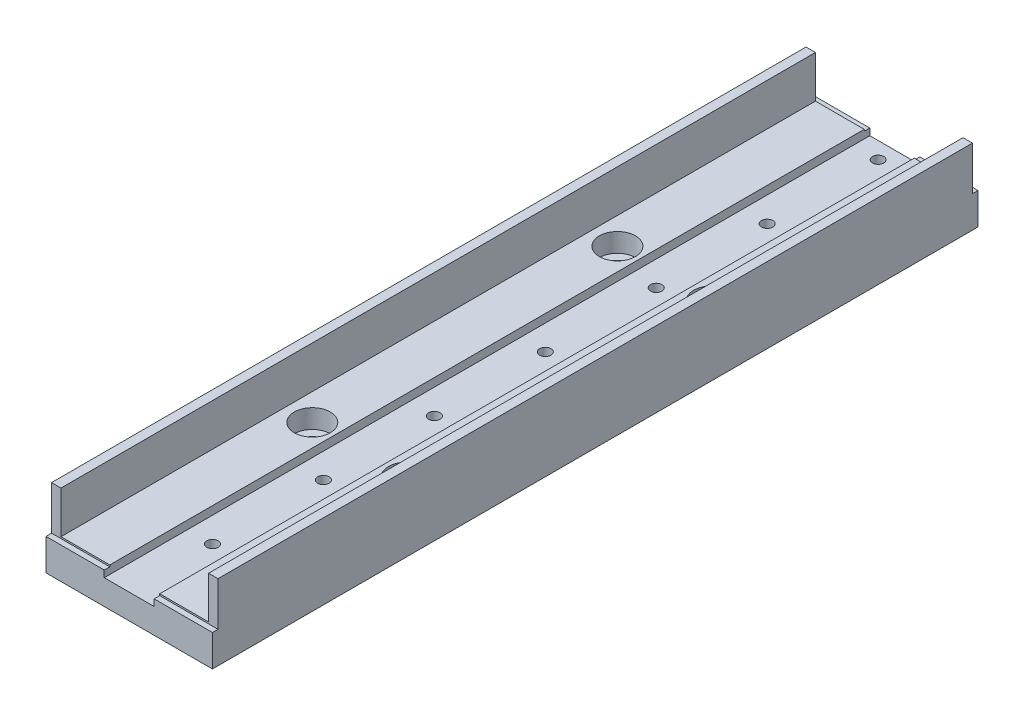
SolidWorks part; units mm, degrees
ref_plane "Спереди" through (0, 0, 0) normal (0, 0, 1) x (1, 0, 0)
ref_plane "Сверху" through (0, 0, 0) normal (0, 1, 0) x (1, 0, 0)
ref_plane "Справа" through (0, 0, 0) normal (1, 0, 0) x (0, 0, -1)
sketch "Эскиз1" plane through (0, 0, 0) normal (0, 0, 1) x (1, 0, 0)
  line L0 (0, 0) -> (0, 13.1204) construction
  line L1 (-15, -3) -> (15, -3)
  line L2 (-15, -3) -> (-15, 3)
  line L3 (-13.3, 3) -> (-4.5, 3)
  line L4 (15, -3) -> (15, 3)
  line L5 (-15, -3) -> (0, 0) construction
  line L6 (0, 0) -> (15, -3) construction
  line L8 (-15, 3) -> (-15, 10.6)
  line L9 (-15, 10.6) -> (-13.3, 10.6)
  line L10 (-13.3, 3) -> (-13.3, 10.6)
  line L11 (15, 10.6) -> (13.3, 10.6)
  line L12 (13.3, 3) -> (13.3, 10.6)
  line L13 (15, 3) -> (15, 10.6)
  line L14 (-4.5, 3) -> (-4.5, 1.5)
  line L15 (-4.5, 1.5) -> (4.5, 1.5)
  line L16 (4.5, 1.5) -> (4.5, 3)
  line L17 (4.5, 3) -> (13.3, 3)
  point P0 (0, 0)
  dimension "D1" = 30
  dimension "D2" = 6
  dimension "D3" = 7.6
  dimension "D4" = 1.7
  dimension "D5" = 9
  dimension "D6" = 1.5
extrude "Body" add sketch "Эскиз1" along normal blind 138
sketch "Эскиз2" plane through (0, 10.6, 0) normal (0, 1, 0) x (1, 0, 0)
  line L0 (15, -138) -> (15, 0) construction
  line L1 (-15, -138) -> (15, -138)
  line L2 (-15, -138) -> (-15, -137)
  line L3 (-15, -137) -> (15, -137)
  line L4 (15, -138) -> (15, -137)
  line L5 (-15, -69) -> (15, -69) construction
  line L6 (-15, -138) -> (-15, 0) construction
  line L7 (15, 0) -> (15, -1)
  line L8 (-15, -1) -> (15, -1)
  line L9 (-15, 0) -> (-15, -1)
  line L10 (-15, 0) -> (15, 0)
  dimension "D1" = 1
extrude "Cut1" cut sketch "Эскиз2" against normal offset from surface (7.9 mm away) 0.3 up to face at (-8.9, 3, 69) offset beyond the face yes
sketch "Эскиз3" plane through (0, 3, 0) normal (0, 1, 0) x (1, 0, 0)
  line L0 (0, 0) -> (0, -138) construction
  line L1 (4.5, -138) -> (-4.5, -138) construction
  line L2 (0, -69) -> (15, -69) construction
  line L3 (15, -137) -> (15, -1) construction
  point P3 (8.5, -41.5)
  point P6 (-8.5, -41.5)
  point P7 (8.5, -96.5)
  point P9 (-8.5, -96.5)
  dimension "D1" = 55
  dimension "D2" = 17
hole_wizard "Fixture M3" positions "Трехмерный эскиз1" profile "Эскиз4" counterbore size "M3" standard "ISO"
sketch3d "Трехмерный эскиз1"
  point P0 (-8.5, 3, 96.5)
  point P3 (8.5, 3, 96.5)
  point P6 (8.5, 3, 41.5)
  point P9 (-8.5, 3, 41.5)
sketch "Эскиз4" plane through (-8.5, 3, 96.5) normal (1, 0, 0) x (0, 0, 1)
  line L0 (0, 0) -> (0, 7.0215)
  line L1 (0, 7.0215) -> (1.7, 6)
  line L2 (1.7, 6) -> (1.7, 3.4)
  line L3 (1.7, 3.4) -> (3.25, 3.4)
  line L4 (3.25, 3.4) -> (3.25, 0)
  line L5 (3.25, 0) -> (0, 0)
  line L10 (0, 7.0215) -> (-1.7, 6) construction
  line L11 (0, -6.35) -> (0, 107.95) construction
  dimension "Диаметр отверстия" = 3.4
  dimension "Глубина отверстия" = 6
  dimension "Диаметр цековки" = 6.5
  dimension "Глубина цековки" = 3.4
  dimension "Угол заточки сверла" = 118
sketch "Эскиз6" plane through (0, 1.5, 0) normal (0, 1, 0) x (1, 0, 0)
  line L0 (0, 0) -> (0, -138) construction
  line L1 (4.5, -138) -> (-4.5, -138) construction
  point P0 (0, -123)
  dimension "D1" = 15
hole_wizard "Fixture M2" positions "Трехмерный эскиз2" profile "Эскиз7" tap size "M2.5" standard "ISO"
sketch3d "Трехмерный эскиз2"
  point P0 (0, 1.5, 123)
sketch "Эскиз7" plane through (0, 1.5, 123) normal (1, 0, 0) x (0, 0, 1)
  line L0 (0, 0) -> (0, 5.1159)
  line L1 (0, 5.1159) -> (1.025, 4.5)
  line L2 (1.025, 4.5) -> (1.025, 0)
  line L5 (1.025, 0) -> (0, 0)
  line L10 (0, 5.1159) -> (-1.025, 4.5) construction
  line L11 (0, -6.35) -> (0, 107.95) construction
  dimension "Диаметр сверла" = 2.05
  dimension "Глубина сверла" = 4.5
  dimension "Угол заточки сверла" = 118
cosmetic thread "Отверстие резьбы4" parameters "D1"=4.5, "D2"=2.5
pattern_linear "Линейный массив1" count 7 spacing 20 along (0, 0, -1) of "Fixture M2"
